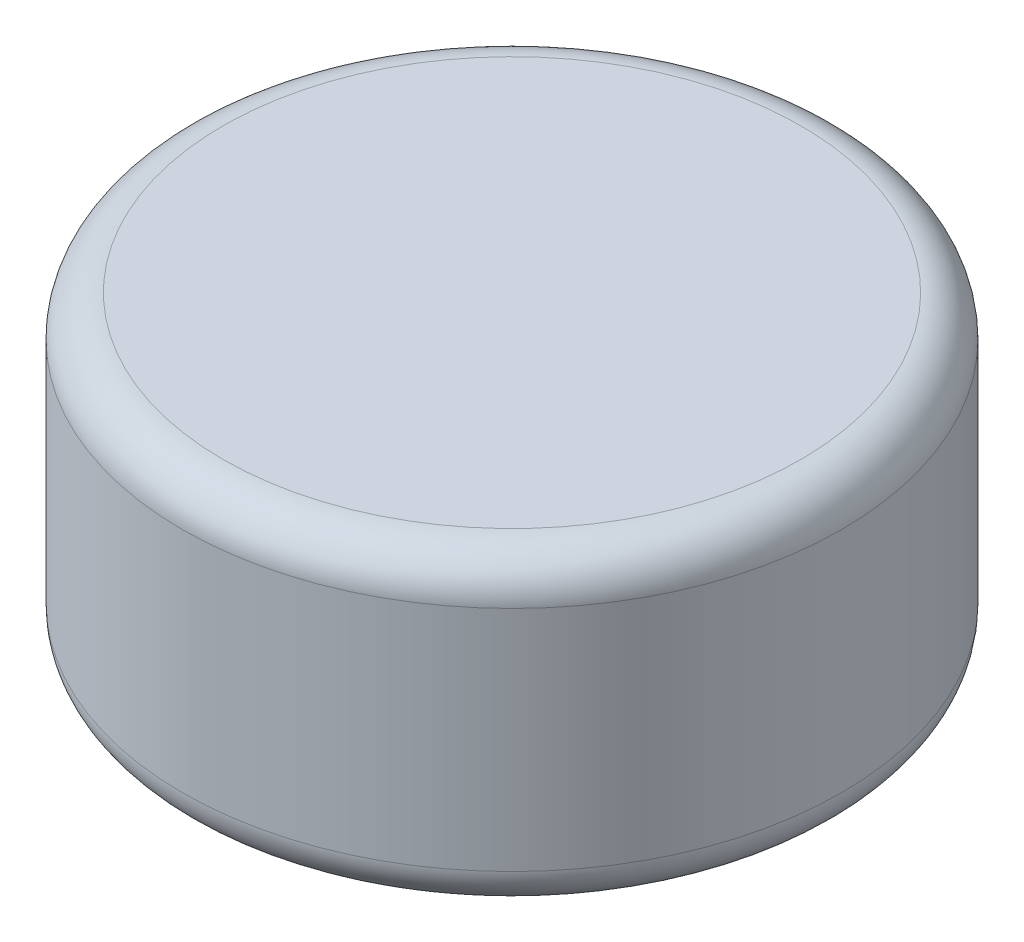
SolidWorks part; units mm, degrees
ref_plane "Front Plane" through (0, 0, 0) normal (0, 0, 1) x (1, 0, 0)
ref_plane "Top Plane" through (0, 0, 0) normal (0, 1, 0) x (1, 0, 0)
ref_plane "Right Plane" through (0, 0, 0) normal (1, 0, 0) x (0, 0, -1)
sketch "Sketch1" plane through (0, 0, 0) normal (0, 1, 0) x (1, 0, 0)
  circle A0 centre (0, 0) radius 40.64
  dimension "D1" = 81.28
extrude "Boss-Extrude1" add sketch "Sketch1" along normal blind 38.1
fillet "Fillet1" radius 5 2 edges at (0, 0, 40.64) (0, 38.1, 40.64)
sketch "Sketch2" plane through (0, 0, 0) normal (0, -1, 0) x (1, 0, 0)
  circle A0 centre (1.587, -0.1187) radius 3.175
extrude "Cut-Extrude1" cut sketch "Sketch2" against normal blind 25.4
